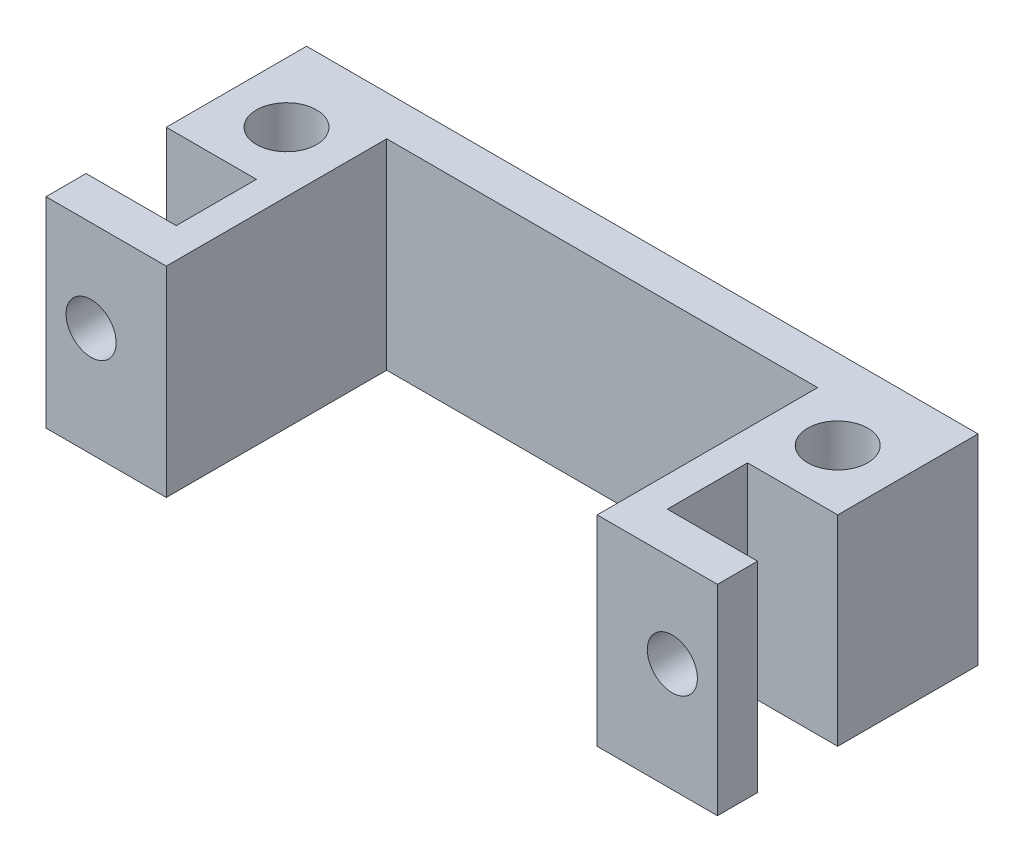
SolidWorks part; units mm, degrees
ref_plane "Front Plane" through (0, 0, 0) normal (0, 0, 1) x (1, 0, 0)
ref_plane "Top Plane" through (0, 0, 0) normal (0, 1, 0) x (1, 0, 0)
ref_plane "Right Plane" through (0, 0, 0) normal (1, 0, 0) x (0, 0, -1)
sketch "Sketch1" plane through (0, 0, 0) normal (0, 1, 0) x (1, 0, 0)
  line L0 (69.85, 0) -> (85.09, 0)
  line L1 (0, 0) -> (15.24, 0)
  line L2 (0, 0) -> (0, 5.08)
  line L3 (0, 33.02) -> (85.09, 33.02)
  line L4 (85.09, 0) -> (85.09, 5.08)
  line L6 (15.24, 0) -> (15.24, 27.94)
  line L7 (15.24, 27.94) -> (69.85, 27.94)
  line L8 (69.85, 0) -> (69.85, 27.94)
  line L9 (0, 15.24) -> (11.43, 15.24)
  line L10 (11.43, 15.24) -> (11.43, 5.08)
  line L11 (11.43, 5.08) -> (0, 5.08)
  line L12 (85.09, 15.24) -> (73.66, 15.24)
  line L13 (73.66, 15.24) -> (73.66, 5.08)
  line L14 (73.66, 5.08) -> (85.09, 5.08)
  line L15 (0, 15.24) -> (0, 33.02)
  line L16 (85.09, 15.24) -> (85.09, 33.02)
  dimension "D1" = 15.24
  dimension "D2" = 15.24
  dimension "D3" = 27.94
  dimension "D4" = 54.61
  dimension "D5" = 5.08
  dimension "D6" = 5.08
  dimension "D7" = 10.16
  dimension "D8" = 3.81
extrude "Boss-Extrude1" add sketch "Sketch1" along normal blind 25.4
sketch "Sketch2" plane through (0, 25.4, 0) normal (0, 1, 0) x (1, 0, 0)
  line L0 (0, 0) -> (15.24, 0) construction
  line L1 (69.85, 0) -> (85.09, 0) construction
  line L2 (85.09, 33.02) -> (0, 33.02) construction
  circle A0 centre (7.62, 22.86) radius 3.81
  circle A1 centre (77.47, 22.86) radius 3.81
  point P6 (7.62, 0)
  point P9 (77.47, 0)
  dimension "D1" = 7.62
  dimension "D2" = 10.16
extrude "Cut-Extrude1" cut sketch "Sketch2" against normal through all
hole_wizard "1/4 (0.25) Diameter Hole1" positions "Sketch3" profile "Sketch4" hole size "1/4" standard "ANSI Inch"
sketch "Sketch3" plane through (0, 0, 0) normal (0, 0, 1) x (1, 0, 0)
  line L0 (5.715, 13.8028) -> (79.375, 13.8028) construction
  line L4 (15.24, 0) -> (69.85, 0) construction
  line L5 (42.545, 13.8028) -> (42.545, 0) construction
  point P0 (5.715, 13.8028)
  point P2 (79.375, 13.8028)
  dimension "D1" = 73.66
sketch "Sketch4" plane through (5.715, 13.8028, 0) normal (1, 0, 0) x (0, -1, 0)
  line L0 (0, 0) -> (0, 9.5277)
  line L1 (0, 9.5277) -> (3.175, 7.62)
  line L2 (3.175, 7.62) -> (3.175, 0)
  line L5 (3.175, 0) -> (0, 0)
  line L10 (0, 9.5277) -> (-3.175, 7.62) construction
  line L11 (0, -6.35) -> (0, 107.95) construction
  dimension "Hole Dia." = 6.35
  dimension "Hole Depth" = 7.62
  dimension "Drill Angle" = 118
hole_wizard "1/4 (0.25) Diameter Hole2" positions "Sketch5" profile "Sketch6" hole size "1/4" standard "ANSI Inch"
sketch "Sketch5" plane through (0, 0, -33.02) normal (0, 0, -1) x (-1, 0, 0)
  line L2 (-85.09, 0) -> (0, 0) construction
  line L3 (-42.545, 0) -> (-42.545, 12.7) construction
  line L11 (-77.47, 12.7) -> (-7.62, 12.7) construction
  point P0 (-77.47, 12.7)
  point P2 (-7.62, 12.7)
  point P42 (-42.545, 12.7)
  dimension "D1" = 69.85
sketch "Sketch6" plane through (77.47, 12.7, -33.02) normal (1, 0, 0) x (0, 1, 0)
  line L0 (0, 0) -> (0, 12.0677)
  line L1 (0, 12.0677) -> (3.175, 10.16)
  line L2 (3.175, 10.16) -> (3.175, 0)
  line L5 (3.175, 0) -> (0, 0)
  line L10 (0, 12.0677) -> (-3.175, 10.16) construction
  line L11 (0, -6.35) -> (0, 107.95) construction
  dimension "Hole Dia." = 6.35
  dimension "Hole Depth" = 10.16
  dimension "Drill Angle" = 118
equation "\"D2@Sketch1\"=\"D1@Sketch1\""
